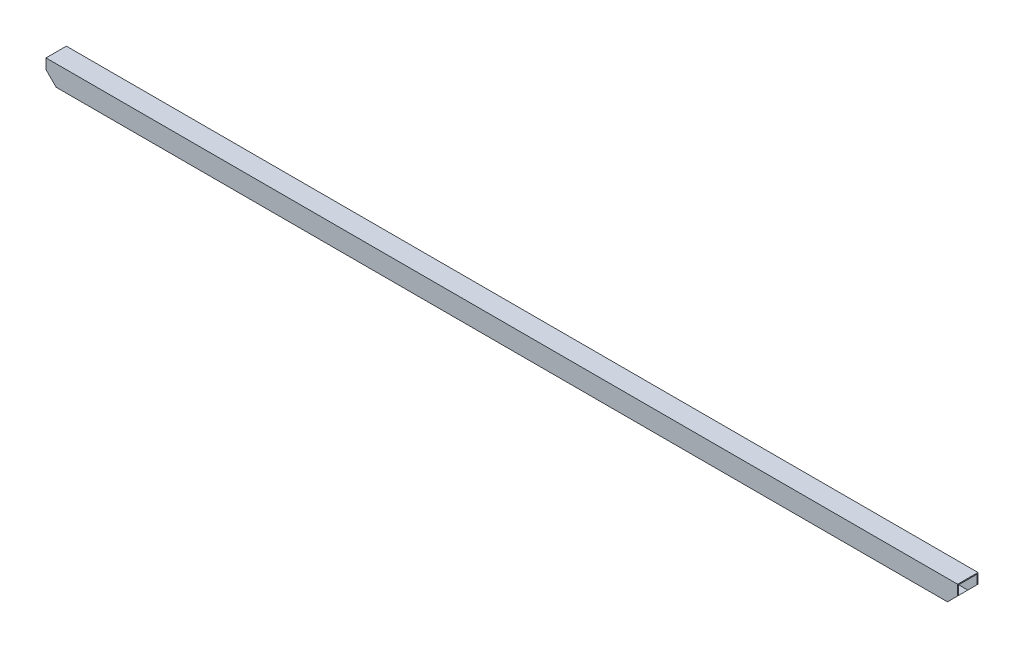
SolidWorks part; units mm, degrees
ref_plane "Front Plane" through (0, 0, 0) normal (0, 0, 1) x (1, 0, 0)
ref_plane "Top Plane" through (0, 0, 0) normal (0, 1, 0) x (1, 0, 0)
ref_plane "Right Plane" through (0, 0, 0) normal (1, 0, 0) x (0, 0, -1)
sketch "Base" plane through (0, 0, 0) normal (0, 1, 0) x (1, 0, 0)
  line L1 (-568.325, -12.7) -> (568.325, -12.7)
  line L2 (-568.325, -12.7) -> (-568.325, 12.7)
  line L3 (-568.325, 12.7) -> (568.325, 12.7)
  line L4 (568.325, -12.7) -> (568.325, 12.7)
  line L5 (-568.325, -12.7) -> (568.325, 12.7) construction
  line L6 (-568.325, 12.7) -> (568.325, -12.7) construction
  point P0 (0, 0)
  dimension "D1" = 1136.65
  dimension "D2" = 25.4
extrude "Boss-Frame" add sketch "Base" along normal blind 25.4
sketch "Sketch2" plane through (568.325, 0, 0) normal (1, 0, 0) x (0, 0, -1)
  line L0 (-12.7, 0) -> (12.7, 25.4) construction
  line L1 (-12.7, 25.4) -> (12.7, 0) construction
  line L3 (-11.43, 1.27) -> (11.43, 1.27)
  line L4 (-11.43, 1.27) -> (-11.43, 24.13)
  line L5 (-11.43, 24.13) -> (11.43, 24.13)
  line L6 (11.43, 1.27) -> (11.43, 24.13)
  line L7 (-11.43, 1.27) -> (11.43, 24.13) construction
  line L8 (-11.43, 24.13) -> (11.43, 1.27) construction
  point P8 (0, 12.7)
  dimension "D1" = 22.86
extrude "Cut-Hollow" cut sketch "Sketch2" against normal through all
sketch "Sketch4" plane through (0, 0, 12.7) normal (0, 0, 1) x (1, 0, 0)
  line L0 (-568.325, 12.7) -> (568.325, 12.7) construction
  line L1 (-568.325, 25.4) -> (-568.325, 0) construction
  line L2 (568.325, 25.4) -> (568.325, 0) construction
  line L3 (-568.325, 12.7) -> (-568.325, 0)
  line L4 (-568.325, 0) -> (-555.6452, 0)
  line L5 (-568.325, 0) -> (568.325, 0) construction
  line L6 (-555.6452, 0) -> (-568.325, 12.7)
  line L7 (0, 25.4) -> (0, 0) construction
  line L8 (-568.325, 25.4) -> (568.325, 25.4) construction
  line L9 (568.325, 0) -> (555.6452, 0)
  line L10 (568.325, 12.7) -> (568.325, 0)
  line L11 (555.6452, 0) -> (568.325, 12.7)
extrude "Cut-Angle" cut sketch "Sketch4" against normal through all
